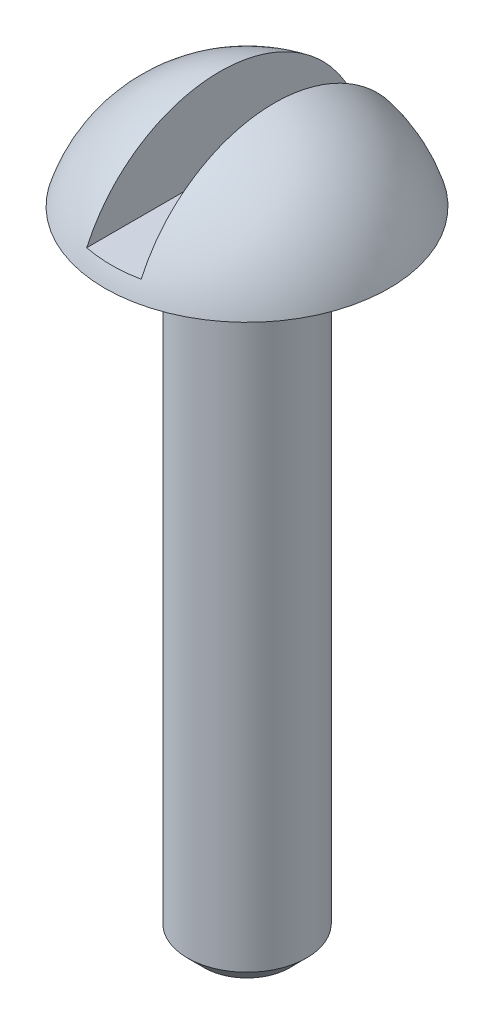
SolidWorks part; units mm, degrees
ref_plane "Front Plane" through (0, 0, 0) normal (0, 0, 1) x (1, 0, 0)
ref_plane "Top Plane" through (0, 0, 0) normal (0, 1, 0) x (1, 0, 0)
ref_plane "Right Plane" through (0, 0, 0) normal (1, 0, 0) x (0, 0, -1)
sketch "Sketch2" plane through (0, 0, 0) normal (1, 0, 0) x (0, 0, -1)
  line L0 (0, 0) -> (2.1209, 0)
  line L1 (0, 0) -> (0, 1.5748)
  line L2 (0, 0.4152) -> (0, -1.08) construction
  arc A0 (2.1209, 0) -> (0, 1.5748) centre (0, -0.6408) ccw
  dimension "D1" = 2.1209
  dimension "D2" = 1.5748
revolve "Revolve1" add sketch "Sketch2" angle 360 about L2
sketch "Sketch3" plane through (0, 0, 0) normal (0, -1, 0) x (1, 0, 0)
  circle A0 centre (0, 0) radius 0.889
  dimension "D1" = 1.778
extrude "Boss-Extrude1" add sketch "Sketch3" along normal blind 9.525
chamfer "Chamfer1" distance 0.254 angle 45 1 edges at (0, -9.525, -0.889)
sketch "Sketch4" plane through (0, 0, 0) normal (0, 1, 0) x (1, 0, 0)
  line L1 (-0.4064, -2.1209) -> (0.4064, -2.1209)
  line L2 (-0.4064, -2.1209) -> (-0.4064, 2.1209)
  line L3 (-0.4064, 2.1209) -> (0.4064, 2.1209)
  line L4 (0.4064, -2.1209) -> (0.4064, 2.1209)
  line L5 (-0.4064, -2.1209) -> (0.4064, 2.1209) construction
  line L6 (-0.4064, 2.1209) -> (0.4064, -2.1209) construction
  circle A0 centre (0, 0) radius 2.1209 construction
  point P0 (0, 0)
  dimension "D1" = 0.8128
extrude "Cut-Extrude1" cut sketch "Sketch4" along normal through all from offset 0.254
